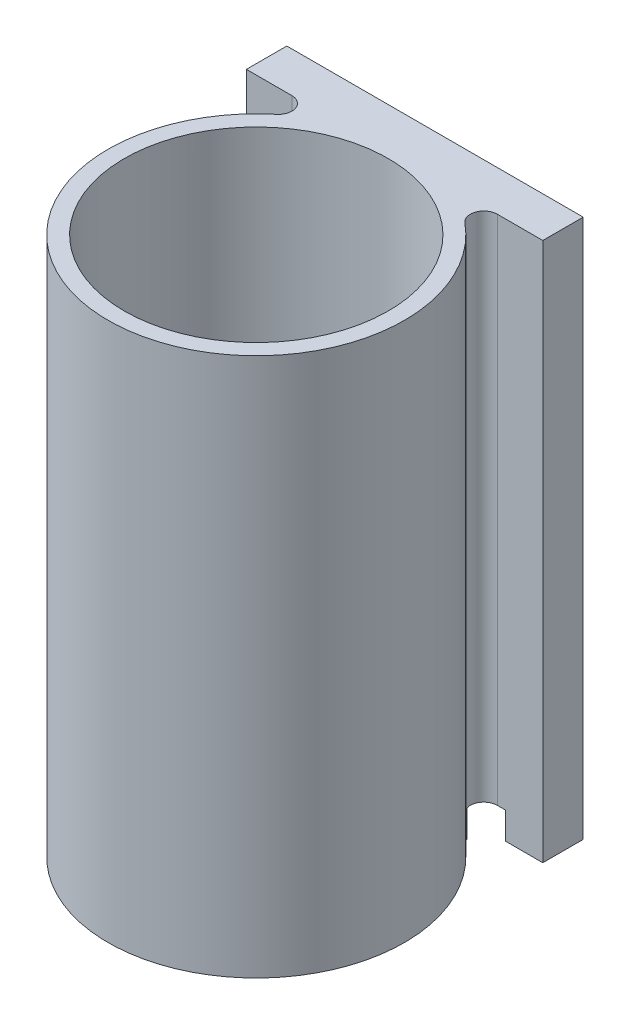
SolidWorks part; units mm, degrees
ref_plane "Спереди" through (0, 0, 0) normal (0, 0, 1) x (1, 0, 0)
ref_plane "Сверху" through (0, 0, 0) normal (0, 1, 0) x (1, 0, 0)
ref_plane "Справа" through (0, 0, 0) normal (1, 0, 0) x (0, 0, -1)
sketch "Эскиз1" plane through (0, 0, 0) normal (0, 0, 1) x (1, 0, 0)
  line L1 (-11, 20) -> (11, 20)
  line L2 (-11, 20) -> (-11, -20)
  line L3 (-11, -20) -> (11, -20)
  line L4 (11, 20) -> (11, -20)
  line L5 (-11, 20) -> (11, -20) construction
  line L6 (-11, -20) -> (11, 20) construction
  point P0 (0, 0)
  dimension "D1" = 22
  dimension "D2" = 40
extrude "Бобышка-Вытянуть1" add sketch "Эскиз1" along normal blind 3
sketch "Эскиз2" plane through (0, 20, 0) normal (0, 1, 0) x (1, 0, 0)
  circle A0 centre (0, -13.2677) radius 11
  circle A1 centre (0, -13.2677) radius 9.8
  point P3 (0, -13.2677)
extrude "Бобышка-Вытянуть2" add sketch "Эскиз2" against normal blind 40
fillet "Скругление1" radius 1 2 edges at (3.9464, 0, 3) (-3.9464, 0, 3)
sketch "Эскиз3" plane through (0, -20, 0) normal (0, -1, 0) x (1, 0, 0)
  line L1 (-8.2314, -4.2954) -> (8.2314, -4.2954)
  line L2 (-8.2314, -4.2954) -> (-8.2314, 4.2954)
  line L3 (-8.2314, 4.2954) -> (8.2314, 4.2954)
  line L4 (8.2314, -4.2954) -> (8.2314, 4.2954)
  line L5 (-8.2314, -4.2954) -> (8.2314, 4.2954) construction
  line L6 (-8.2314, 4.2954) -> (8.2314, -4.2954) construction
  point P0 (0, 0)
extrude "Вырез-Вытянуть1" cut sketch "Эскиз3" against normal blind 2
